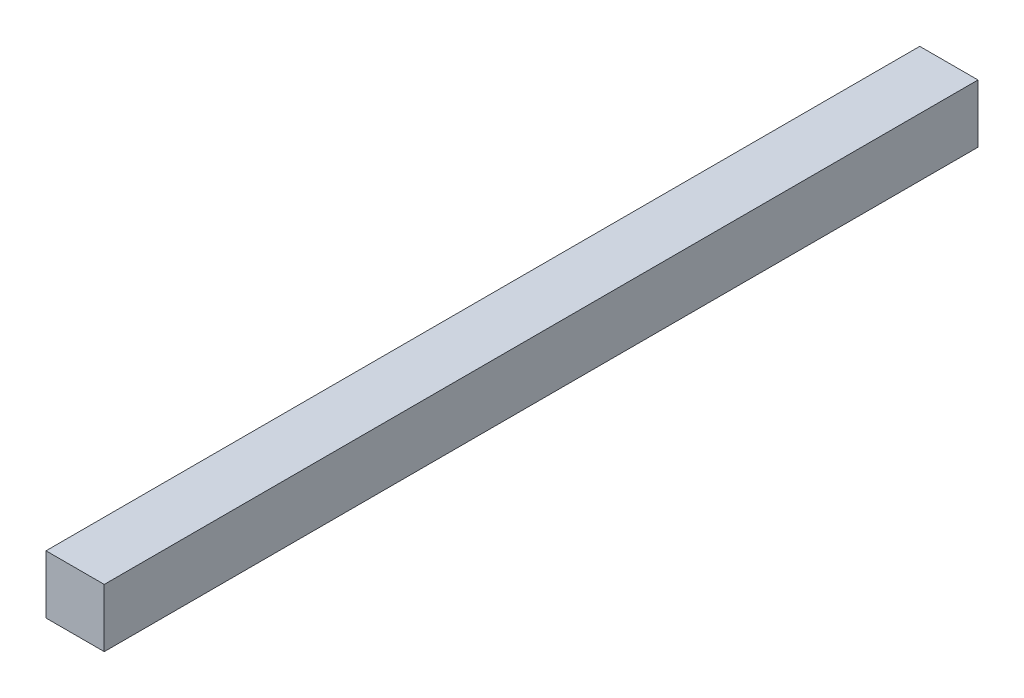
SolidWorks part; units mm, degrees
ref_plane "前基準面" through (0, 0, 0) normal (0, 0, 1) x (1, 0, 0)
ref_plane "上基準面" through (0, 0, 0) normal (0, 1, 0) x (1, 0, 0)
ref_plane "右基準面" through (0, 0, 0) normal (1, 0, 0) x (0, 0, -1)
sketch "草圖1" plane through (0, 0, 0) normal (0, 0, 1) x (1, 0, 0)
  line L1 (-10, 10) -> (10, 10)
  line L2 (-10, 10) -> (-10, -10)
  line L3 (-10, -10) -> (10, -10)
  line L4 (10, 10) -> (10, -10)
  point P4 (0, 10)
  point P6 (-10, 0)
  dimension "D1" = 20
  dimension "D2" = 20
extrude "填料-伸長1" add sketch "草圖1" along normal blind 300
sketch "草圖2" plane through (0, 10, 0) normal (0, 1, 0) x (1, 0, 0)
  line L0 (-10, -50) -> (10, -50)
  line L1 (-10, -300) -> (-10, 0) construction
  line L2 (10, -300) -> (10, 0) construction
  line L3 (10, 0) -> (-10, 0) construction
  line L4 (-10, -100) -> (10, -100)
  line L5 (-10, -150) -> (10, -150)
  line L6 (-10, -200) -> (10, -200)
  line L7 (-10, -250) -> (10, -250)
  dimension "D1" = 50
  dimension "D2" = 5
sketch "草圖3" plane through (10, 0, 0) normal (1, 0, 0) x (0, 0, -1)
  line L0 (-20, 10) -> (-20, -10) construction
  line L4 (-300, 10) -> (0, 10) construction
  line L5 (-300, -10) -> (0, -10) construction
  line L6 (0, -10) -> (0, 10) construction
  line L7 (-70, 10) -> (-70, -10)
  line L8 (-150, 10) -> (-150, -10) construction
  line L9 (-230, 10) -> (-230, -10)
  dimension "D1" = 20
  dimension "D2" = 70
